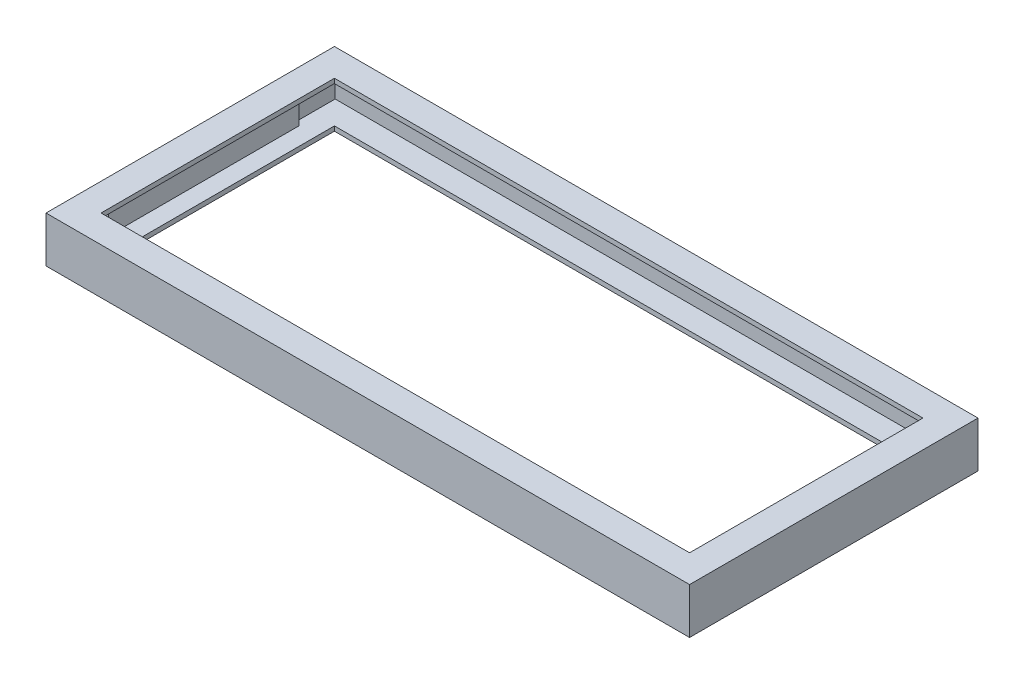
SolidWorks part; units mm, degrees
ref_plane "Front" through (0, 0, 0) normal (0, 0, 1) x (1, 0, 0)
ref_plane "Top" through (0, 0, 0) normal (0, 1, 0) x (1, 0, 0)
ref_plane "Right" through (0, 0, 0) normal (1, 0, 0) x (0, 0, -1)
sketch "Sketch7" plane through (0, 0, 0) normal (0, 1, 0) x (1, 0, 0)
  line L1 (0, 0) -> (11.1243, 0)
  line L2 (0, 0) -> (0, 62.8948)
  line L3 (0, 62.8948) -> (11.1243, 62.8948)
  line L4 (11.1243, 11.5521) -> (11.1243, 53.0541)
  line L5 (11.1243, 62.8948) -> (131.3518, 62.8948)
  line L7 (11.1243, 53.0541) -> (131.3518, 53.0541)
  line L9 (131.3518, 62.8948) -> (140.3368, 62.8948)
  line L10 (131.3518, 53.0541) -> (131.3518, 11.5521)
  line L11 (131.3518, 0) -> (140.3368, 0)
  line L12 (140.3368, 62.8948) -> (140.3368, 0)
  line L13 (11.1243, 0) -> (131.3518, 0)
  line L15 (11.1243, 11.5521) -> (131.3518, 11.5521)
extrude "Boss-Extrude4" add sketch "Sketch7" along normal blind 10
sketch "Sketch9" plane through (11.1243, 0, 0) normal (1, 0, 0) x (0, 0, -1)
  line L0 (62.8948, 10) -> (0, 10) construction
  line L1 (1, 9) -> (61.8948, 9)
  line L2 (1, 9) -> (1, 1)
  line L3 (1, 1) -> (61.8948, 1)
  line L4 (61.8948, 9) -> (61.8948, 1)
  line L5 (62.8948, 0) -> (0, 0) construction
  line L6 (0, 10) -> (0, 0) construction
  line L7 (62.8948, 10) -> (62.8948, 0) construction
  dimension "D1" = 1
  dimension "D2" = 1
  dimension "D3" = 1
  dimension "D4" = 1
extrude "Cut-Extrude4" cut sketch "Sketch9" against normal blind 9
sketch "Sketch12" plane through (131.3518, 0, 0) normal (-1, 0, 0) x (0, 0, 1)
  line L0 (-62.8948, 10) -> (0, 10) construction
  line L1 (-61.8948, 9) -> (-1, 9)
  line L2 (-61.8948, 9) -> (-61.8948, 1)
  line L3 (-61.8948, 1) -> (-1, 1)
  line L4 (-1, 9) -> (-1, 1)
  line L5 (-62.8948, 0) -> (0, 0) construction
  line L6 (-62.8948, 10) -> (-62.8948, 0) construction
  line L7 (0, 10) -> (0, 0) construction
  dimension "D1" = 1
  dimension "D2" = 1
  dimension "D3" = 1
  dimension "D4" = 1
extrude "Cut-Extrude6" cut sketch "Sketch12" against normal blind 8
sketch "Sketch14" plane through (0, 0, -53.0541) normal (0, 0, 1) x (1, 0, 0)
  line L0 (0, 10) -> (140.3368, 10) construction
  line L1 (1, 9) -> (139.3368, 9)
  line L2 (1, 9) -> (1, 1)
  line L3 (1, 1) -> (139.3368, 1)
  line L4 (139.3368, 9) -> (139.3368, 1)
  line L5 (0, 0) -> (140.3368, 0) construction
  line L6 (140.3368, 10) -> (140.3368, 0) construction
  line L7 (0, 10) -> (0, 0) construction
  dimension "D1" = 1
  dimension "D2" = 1
  dimension "D3" = 1
  dimension "D4" = 1
extrude "Cut-Extrude7" cut sketch "Sketch14" against normal blind 9
sketch "Sketch17" plane through (0, 0, -11.5521) normal (0, 0, -1) x (-1, 0, 0)
  line L0 (-140.3368, 10) -> (0, 10) construction
  line L1 (-139.3368, 9) -> (-1, 9)
  line L2 (-139.3368, 9) -> (-139.3368, 1)
  line L3 (-139.3368, 1) -> (-1, 1)
  line L4 (-1, 9) -> (-1, 1)
  line L5 (-140.3368, 0) -> (0, 0) construction
  line L6 (-140.3368, 10) -> (-140.3368, 0) construction
  line L7 (0, 10) -> (0, 0) construction
  dimension "D1" = 1
  dimension "D2" = 1
  dimension "D3" = 1
  dimension "D4" = 1
extrude "Cut-Extrude8" cut sketch "Sketch17" against normal blind 9
sketch "Sketch20" plane through (0, 10, 0) normal (0, 1, 0) x (1, 0, 0)
  line L0 (0, 62.8948) -> (0, 0) construction
  line L1 (6, 56.8948) -> (134.3368, 56.8948)
  line L2 (6, 56.8948) -> (6, 6)
  line L3 (6, 6) -> (134.3368, 6)
  line L4 (134.3368, 56.8948) -> (134.3368, 6)
  line L5 (140.3368, 62.8948) -> (0, 62.8948) construction
  line L6 (140.3368, 0) -> (140.3368, 62.8948) construction
  line L7 (0, 0) -> (140.3368, 0) construction
  dimension "D1" = 6
  dimension "D2" = 6
  dimension "D3" = 6
  dimension "D4" = 6
extrude "Cut-Extrude10" cut sketch "Sketch20" against normal blind 10
